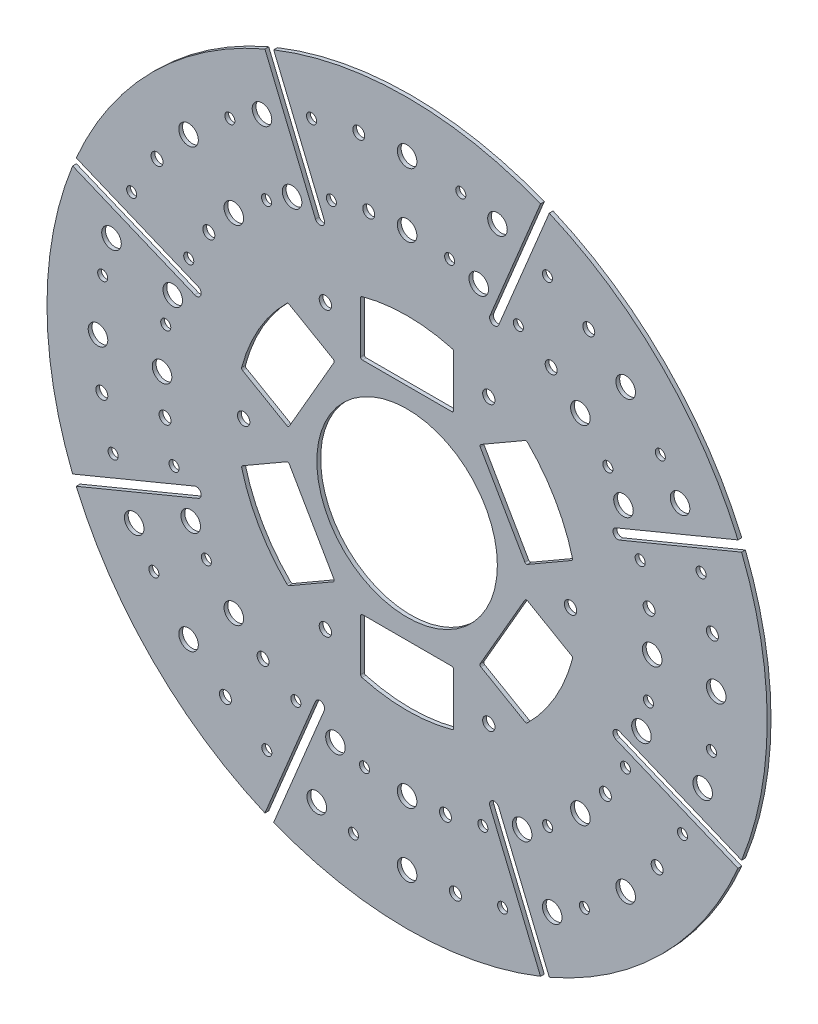
SolidWorks part; units mm, degrees
ref_plane "Plano frontal" through (0, 0, 0) normal (0, 0, 1) x (1, 0, 0)
ref_plane "Plano superior" through (0, 0, 0) normal (0, 1, 0) x (1, 0, 0)
ref_plane "Plano direito" through (0, 0, 0) normal (1, 0, 0) x (0, 0, -1)
sketch "Esboço1" plane through (0, 0, 0) normal (0, 0, 1) x (1, 0, 0)
  circle A0 centre (0, 0) radius 189.5
  circle A1 centre (0, 0) radius 47.5
extrude "Ressalto-extrusão1" add sketch "Esboço1" along normal blind 2
sketch "Esboço2" plane through (0, 0, 2) normal (0, 0, 1) x (1, 0, 0)
  line L1 (70.2088, 176.0319) -> (74.8282, 174.1185)
  line L4 (70.2088, 176.0319) -> (43.6023, 111.7982)
  line L5 (74.8282, 174.1185) -> (48.2217, 109.8848)
  line L9 (174.1185, 74.8282) -> (176.0319, 70.2088)
  line L10 (174.1185, 74.8282) -> (109.8848, 48.2217)
  line L11 (176.0319, 70.2088) -> (111.7982, 43.6023)
  line L15 (176.0319, -70.2088) -> (174.1185, -74.8282)
  line L16 (176.0319, -70.2088) -> (111.7982, -43.6023)
  line L17 (174.1185, -74.8282) -> (109.8848, -48.2217)
  line L21 (74.8282, -174.1185) -> (70.2088, -176.0319)
  line L22 (74.8282, -174.1185) -> (48.2217, -109.8848)
  line L23 (70.2088, -176.0319) -> (43.6023, -111.7982)
  line L27 (-70.2088, -176.0319) -> (-74.8282, -174.1185)
  line L28 (-70.2088, -176.0319) -> (-43.6023, -111.7982)
  line L29 (-74.8282, -174.1185) -> (-48.2217, -109.8848)
  line L33 (-174.1185, -74.8282) -> (-176.0319, -70.2088)
  line L34 (-174.1185, -74.8282) -> (-109.8848, -48.2217)
  line L35 (-176.0319, -70.2088) -> (-111.7982, -43.6023)
  line L39 (-176.0319, 70.2088) -> (-174.1185, 74.8282)
  line L40 (-176.0319, 70.2088) -> (-111.7982, 43.6023)
  line L41 (-174.1185, 74.8282) -> (-109.8848, 48.2217)
  line L45 (-74.8282, 174.1185) -> (-70.2088, 176.0319)
  line L46 (-74.8282, 174.1185) -> (-48.2217, 109.8848)
  line L47 (-70.2088, 176.0319) -> (-43.6023, 111.7982)
  arc A0 (43.6023, 111.7982) -> (48.2217, 109.8848) centre (45.912, 110.8415) ccw
  arc A2 (109.8848, 48.2217) -> (111.7982, 43.6023) centre (110.8415, 45.912) ccw
  arc A5 (111.7982, -43.6023) -> (109.8848, -48.2217) centre (110.8415, -45.912) ccw
  arc A7 (48.2217, -109.8848) -> (43.6023, -111.7982) centre (45.912, -110.8415) ccw
  arc A9 (-43.6023, -111.7982) -> (-48.2217, -109.8848) centre (-45.912, -110.8415) ccw
  arc A11 (-109.8848, -48.2217) -> (-111.7982, -43.6023) centre (-110.8415, -45.912) ccw
  arc A13 (-111.7982, 43.6023) -> (-109.8848, 48.2217) centre (-110.8415, 45.912) ccw
  arc A15 (-48.2217, 109.8848) -> (-43.6023, 111.7982) centre (-45.912, 110.8415) ccw
  point P82 (0, 0)
extrude "Corte-extrusão1" cut sketch "Esboço2" against normal blind 2
sketch "Esboço3" plane through (0, 0, 2) normal (0, 0, 1) x (1, 0, 0)
  line L0 (0, 0) -> (0, 189.5) construction
  line L1 (0, 0) -> (-25.445, 160.6534) construction
  line L2 (0, 0) -> (-50.2635, 154.695) construction
  line L3 (0, 0) -> (28.2449, 160.1848) construction
  line L4 (0, 0) -> (47.556, 155.5487) construction
  line L5 (0, 0) -> (44.9553, 108.5318) construction
  arc A0 (70.2025, 176.0166) -> (-70.2025, 176.0166) centre (0, 0) ccw construction
  circle A1 centre (0, 0) radius 162.6559 construction
  circle A2 centre (0, 0) radius 128.9586 construction
  arc A3 (43.6023, 111.7982) -> (48.2217, 109.8848) centre (45.912, 110.8415) ccw construction
  circle A4 centre (-50.2635, 154.695) radius 2.65
  circle A5 centre (-25.445, 160.6534) radius 3.15
  circle A6 centre (0, 162.6559) radius 5.15
  circle A7 centre (28.2449, 160.1848) radius 2.65
  circle A8 centre (47.556, 155.5487) radius 5.15
  circle A9 centre (37.7038, 123.3237) radius 5.15
  circle A10 centre (22.3934, 126.9994) radius 2.65
  circle A11 centre (0, 128.9586) radius 5.15
  circle A12 centre (-20.1736, 127.3709) radius 3.15
  circle A13 centre (-39.8504, 122.6469) radius 2.65
  circle A14 centre (73.8443, 144.9275) radius 2.65
  circle A15 centre (95.6068, 131.5914) radius 3.15
  circle A16 centre (115.0151, 115.0151) radius 5.15
  circle A17 centre (133.24, 93.2956) radius 2.65
  circle A18 centre (143.6167, 76.3623) radius 5.15
  circle A19 centre (113.8637, 60.5424) radius 5.15
  circle A20 centre (105.6367, 73.9676) radius 2.65
  circle A21 centre (91.1875, 91.1875) radius 5.15
  circle A22 centre (75.7999, 104.3297) radius 3.15
  circle A23 centre (58.546, 114.9029) radius 2.65
  circle A24 centre (154.695, 50.2635) radius 2.65
  circle A25 centre (160.6534, 25.445) radius 3.15
  circle A26 centre (162.6559, 0) radius 5.15
  circle A27 centre (160.1848, -28.2449) radius 2.65
  circle A28 centre (155.5487, -47.556) radius 5.15
  circle A29 centre (123.3237, -37.7038) radius 5.15
  circle A30 centre (126.9994, -22.3934) radius 2.65
  circle A31 centre (128.9586, 0) radius 5.15
  circle A32 centre (127.3709, 20.1736) radius 3.15
  circle A33 centre (122.6469, 39.8504) radius 2.65
  circle A34 centre (144.9275, -73.8443) radius 2.65
  circle A35 centre (131.5914, -95.6068) radius 3.15
  circle A36 centre (115.0151, -115.0151) radius 5.15
  circle A37 centre (93.2956, -133.24) radius 2.65
  circle A38 centre (76.3623, -143.6167) radius 5.15
  circle A39 centre (60.5424, -113.8637) radius 5.15
  circle A40 centre (73.9676, -105.6367) radius 2.65
  circle A41 centre (91.1875, -91.1875) radius 5.15
  circle A42 centre (104.3297, -75.7999) radius 3.15
  circle A43 centre (114.9029, -58.546) radius 2.65
  circle A44 centre (50.2635, -154.695) radius 2.65
  circle A45 centre (25.445, -160.6534) radius 3.15
  circle A46 centre (0, -162.6559) radius 5.15
  circle A47 centre (-28.2449, -160.1848) radius 2.65
  circle A48 centre (-47.556, -155.5487) radius 5.15
  circle A49 centre (-37.7038, -123.3237) radius 5.15
  circle A50 centre (-22.3934, -126.9994) radius 2.65
  circle A51 centre (0, -128.9586) radius 5.15
  circle A52 centre (20.1736, -127.3709) radius 3.15
  circle A53 centre (39.8504, -122.6469) radius 2.65
  circle A54 centre (-73.8443, -144.9275) radius 2.65
  circle A55 centre (-95.6068, -131.5914) radius 3.15
  circle A56 centre (-115.0151, -115.0151) radius 5.15
  circle A57 centre (-133.24, -93.2956) radius 2.65
  circle A58 centre (-143.6167, -76.3623) radius 5.15
  circle A59 centre (-113.8637, -60.5424) radius 5.15
  circle A60 centre (-105.6367, -73.9676) radius 2.65
  circle A61 centre (-91.1875, -91.1875) radius 5.15
  circle A62 centre (-75.7999, -104.3297) radius 3.15
  circle A63 centre (-58.546, -114.9029) radius 2.65
  circle A64 centre (-154.695, -50.2635) radius 2.65
  circle A65 centre (-160.6534, -25.445) radius 3.15
  circle A66 centre (-162.6559, 0) radius 5.15
  circle A67 centre (-160.1848, 28.2449) radius 2.65
  circle A68 centre (-155.5487, 47.556) radius 5.15
  circle A69 centre (-123.3237, 37.7038) radius 5.15
  circle A70 centre (-126.9994, 22.3934) radius 2.65
  circle A71 centre (-128.9586, 0) radius 5.15
  circle A72 centre (-127.3709, -20.1736) radius 3.15
  circle A73 centre (-122.6469, -39.8504) radius 2.65
  circle A74 centre (-144.9275, 73.8443) radius 2.65
  circle A75 centre (-131.5914, 95.6068) radius 3.15
  circle A76 centre (-115.0151, 115.0151) radius 5.15
  circle A77 centre (-93.2956, 133.24) radius 2.65
  circle A78 centre (-76.3623, 143.6167) radius 5.15
  circle A79 centre (-60.5424, 113.8637) radius 5.15
  circle A80 centre (-73.9676, 105.6367) radius 2.65
  circle A81 centre (-91.1875, 91.1875) radius 5.15
  circle A82 centre (-104.3297, 75.7999) radius 3.15
  circle A83 centre (-114.9029, 58.546) radius 2.65
  point P174 (0, 0)
  dimension "D5" = 5.3
  dimension "D6" = 6.3
  dimension "D7" = 10.3
  dimension "D8" = 5.3
  dimension "D9" = 10.3
  dimension "D1" = 9
  dimension "D2" = 9
  dimension "D3" = 10
  dimension "D4" = 7
extrude "Corte-extrusão2" cut sketch "Esboço3" against normal blind 2
sketch "Esboço4" plane through (0, 0, 2) normal (0, 0, 1) x (1, 0, 0)
  line L0 (37.9795, 50.2176) -> (62.4795, 7.7824)
  line L1 (-24.5, 58) -> (24.5, 58)
  line L2 (-24.5, 58) -> (-24.5, 86.6011)
  line L3 (24.5, 58) -> (24.5, 86.6011)
  line L4 (37.9795, 50.2176) -> (62.7487, 64.5182)
  line L5 (62.4795, 7.7824) -> (87.2487, 22.0829)
  line L6 (62.4795, -7.7824) -> (37.9795, -50.2176)
  line L7 (62.4795, -7.7824) -> (87.2487, -22.0829)
  line L8 (37.9795, -50.2176) -> (62.7487, -64.5182)
  line L9 (24.5, -58) -> (-24.5, -58)
  line L10 (24.5, -58) -> (24.5, -86.6011)
  line L11 (-24.5, -58) -> (-24.5, -86.6011)
  line L12 (-37.9795, -50.2176) -> (-62.4795, -7.7824)
  line L13 (-37.9795, -50.2176) -> (-62.7487, -64.5182)
  line L14 (-62.4795, -7.7824) -> (-87.2487, -22.0829)
  line L15 (-62.4795, 7.7824) -> (-37.9795, 50.2176)
  line L16 (-62.4795, 7.7824) -> (-87.2487, 22.0829)
  line L17 (-37.9795, 50.2176) -> (-62.7487, 64.5182)
  arc A0 (62.7487, 64.5182) -> (87.2487, 22.0829) centre (0, 0) cw
  arc A1 (-24.5, 86.6011) -> (24.5, 86.6011) centre (0, 0) cw
  arc A2 (87.2487, -22.0829) -> (62.7487, -64.5182) centre (0, 0) cw
  arc A3 (24.5, -86.6011) -> (-24.5, -86.6011) centre (0, 0) cw
  arc A4 (-62.7487, -64.5182) -> (-87.2487, -22.0829) centre (0, 0) cw
  arc A5 (-87.2487, 22.0829) -> (-62.7487, 64.5182) centre (0, 0) cw
  point P28 (0, 0)
extrude "Corte-extrusão3" cut sketch "Esboço4" against normal blind 2
sketch "Esboço5" plane through (0, 0, 2) normal (0, 0, 1) x (1, 0, 0)
  circle A2 centre (43, 74.4782) radius 3.25
  circle A4 centre (86, 0) radius 3.25
  circle A6 centre (43, -74.4782) radius 3.25
  circle A8 centre (-43, -74.4782) radius 3.25
  circle A10 centre (-86, 0) radius 3.25
  circle A12 centre (-43, 74.4782) radius 3.25
  point P29 (0, 0)
extrude "Corte-extrusão4" cut sketch "Esboço5" against normal blind 2
fillet "Filete1" radius 1 24 edges at (-37.9795, -50.2176, 1) (-62.7487, -64.5182, 1) (-87.2487, -22.0829, 1) (-62.4795, -7.7824, 1) (24.5, -58, 1) (-24.5, -58, 1) (-24.5, -86.6011, 1) (24.5, -86.6011, 1) (62.7487, -64.5182, 1) (37.9795, -50.2176, 1) (62.4795, -7.7824, 1) (87.2487, -22.0829, 1) (37.9795, 50.2176, 1) (62.7487, 64.5182, 1) (62.4795, 7.7824, 1) (87.2487, 22.0829, 1) (24.5, 86.6011, 1) (-24.5, 86.6011, 1) (-24.5, 58, 1) (24.5, 58, 1) (-62.4795, 7.7824, 1) (-87.2487, 22.0829, 1) (-37.9795, 50.2176, 1) (-62.7487, 64.5182, 1)
